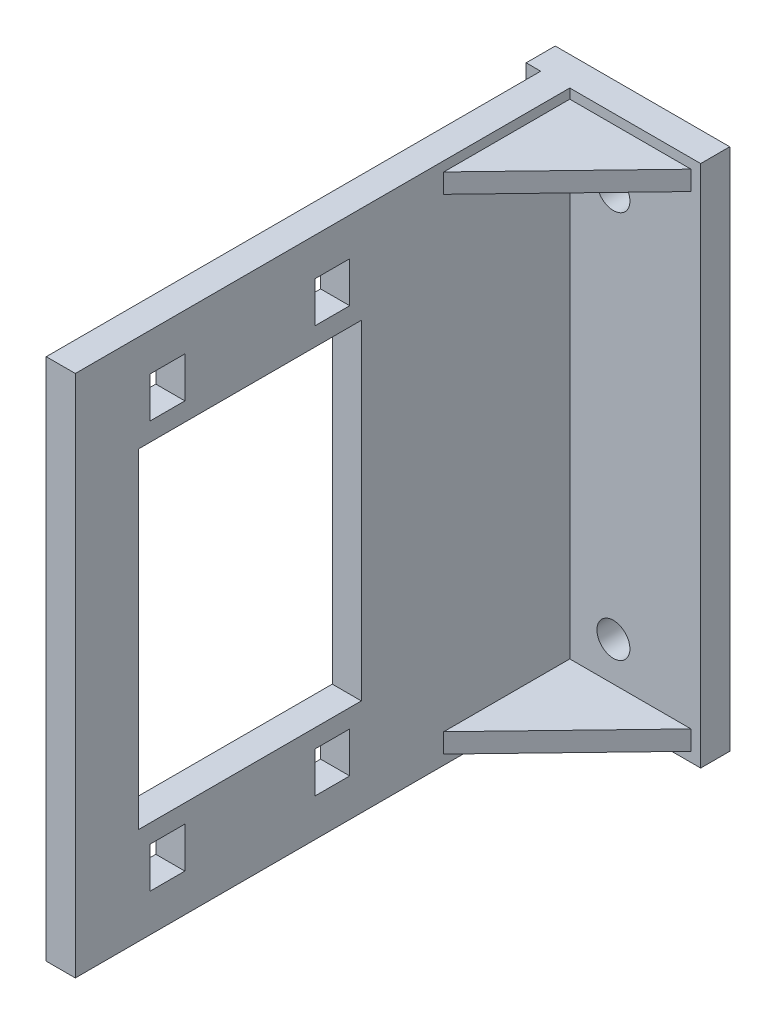
SolidWorks part; units mm, degrees
ref_plane "前视基准面" through (0, 0, 0) normal (0, 0, 1) x (1, 0, 0)
ref_plane "上视基准面" through (0, 0, 0) normal (0, 1, 0) x (1, 0, 0)
ref_plane "右视基准面" through (0, 0, 0) normal (1, 0, 0) x (0, 0, -1)
other "Configuration Table"
sketch "草图1" plane through (0, 0, 0) normal (0, 0, 1) x (1, 0, 0)
  line L0 (-9, -27) -> (9, -27)
  line L1 (9, -27) -> (9, 27)
  line L2 (9, 27) -> (-9, 27)
  line L3 (-9, 27) -> (-9, -27)
extrude "Foot" add sketch "草图1" along normal blind 3 from offset 0
sketch "草图2" plane through (0, 0, 0) normal (0, 0, 1) x (1, 0, 0)
  line L0 (-7.5, -27) -> (-4.5, -27)
  line L1 (-4.5, -27) -> (-4.5, 27)
  line L2 (-4.5, 27) -> (-7.5, 27)
  line L3 (-7.5, 27) -> (-7.5, -27)
extrude "Upright" add sketch "草图2" along normal blind 51 from offset 3
sketch "草图3" plane through (0, 0, 0) normal (1, 0, 0) x (0, 0, -1)
  line L0 (-24.5, -17) -> (-24.5, 17)
  line L1 (-24.5, 17) -> (-47.5, 17)
  line L2 (-47.5, 17) -> (-47.5, -17)
  line L3 (-47.5, -17) -> (-24.5, -17)
extrude "Rear_components_open_window" cut sketch "草图3" along normal blind 5 from offset 8
sketch "草图4" plane through (0, 0, 0) normal (1, 0, 0) x (0, 0, -1)
  line L0 (-25.7, -23.1) -> (-25.7, -18.9)
  line L1 (-25.7, -18.9) -> (-29.3, -18.9)
  line L2 (-29.3, -18.9) -> (-29.3, -23.1)
  line L3 (-29.3, -23.1) -> (-25.7, -23.1)
  line L4 (-42.7, -23.1) -> (-42.7, -18.9)
  line L5 (-42.7, -18.9) -> (-46.3, -18.9)
  line L6 (-46.3, -18.9) -> (-46.3, -23.1)
  line L7 (-46.3, -23.1) -> (-42.7, -23.1)
  line L8 (-25.7, 18.9) -> (-25.7, 23.1)
  line L9 (-25.7, 23.1) -> (-29.3, 23.1)
  line L10 (-29.3, 23.1) -> (-29.3, 18.9)
  line L11 (-29.3, 18.9) -> (-25.7, 18.9)
  line L12 (-42.7, 18.9) -> (-42.7, 23.1)
  line L13 (-42.7, 23.1) -> (-46.3, 23.1)
  line L14 (-46.3, 23.1) -> (-46.3, 18.9)
  line L15 (-46.3, 18.9) -> (-42.7, 18.9)
extrude "Sensor_M2_slots_centres42x17" cut sketch "草图4" along normal blind 5 from offset 8
sketch "草图5" plane through (0, 0, 0) normal (0, 1, 0) x (1, 0, 0)
  line L0 (-4.5, -3) -> (8, -3)
  line L1 (8, -3) -> (-4.5, -16)
  line L2 (-4.5, -16) -> (-4.5, -3)
extrude "Side_gusset" add sketch "草图5" along normal blind 2 from offset 26
sketch "草图6" plane through (0, 0, 0) normal (0, 1, 0) x (1, 0, 0)
  line L0 (-4.5, -3) -> (8, -3)
  line L1 (8, -3) -> (-4.5, -16)
  line L2 (-4.5, -16) -> (-4.5, -3)
extrude "凸台-拉伸4" add sketch "草图6" along normal blind 2 from offset 24
sketch "草图7" plane through (0, 0, 0) normal (0, 0, 1) x (1, 0, 0)
  circle A0 centre (0, -20) radius 1.7
  circle A1 centre (0, 20) radius 1.7
extrude "Foot_M3_holes_pitch40" cut sketch "草图7" along normal blind 3.2 from offset 0.1
